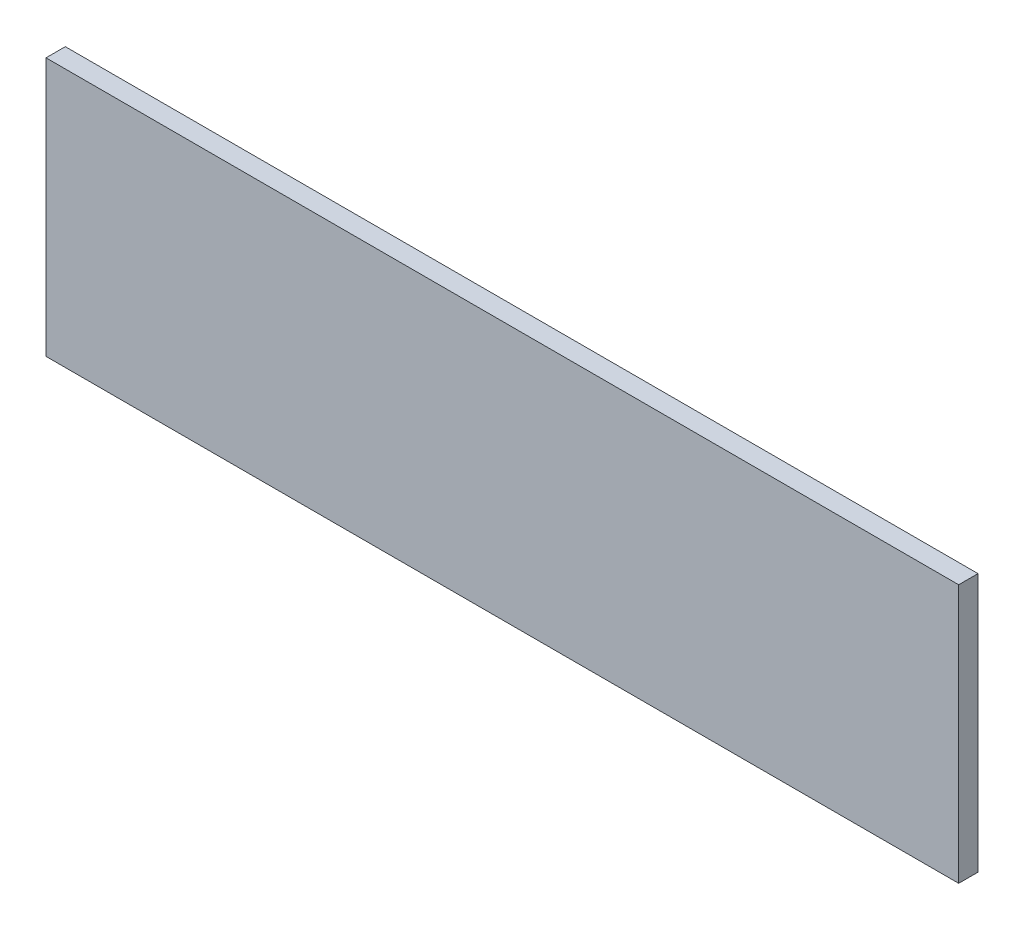
SolidWorks part; units mm, degrees
material "Aleación 1060"
ref_plane "Alzado" through (0, 0, 0) normal (0, 0, 1) x (1, 0, 0)
ref_plane "Planta" through (0, 0, 0) normal (0, 1, 0) x (1, 0, 0)
ref_plane "Vista lateral" through (0, 0, 0) normal (1, 0, 0) x (0, 0, -1)
sketch "Croquis1" plane through (0, 0, 0) normal (0, 0, 1) x (1, 0, 0)
  line L1 (-300, -85) -> (300, -85)
  line L2 (-300, -85) -> (-300, 85)
  line L3 (-300, 85) -> (300, 85)
  line L4 (300, -85) -> (300, 85)
  line L5 (-300, -85) -> (300, 85) construction
  line L6 (-300, 85) -> (300, -85) construction
  point P0 (0, 0)
  dimension "D1" = 170
  dimension "D2" = 600
extrude "Saliente-Extruir1" add sketch "Croquis1" along normal blind 12.7
